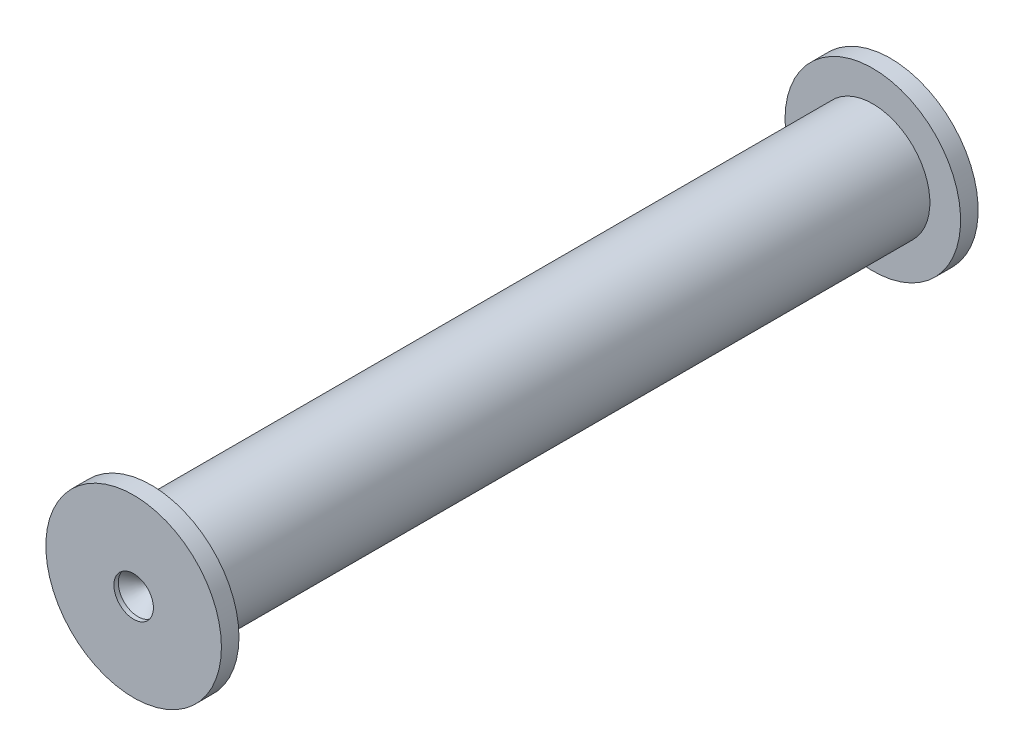
SolidWorks part; units mm, degrees
ref_plane "Ön Düzlem" through (0, 0, 0) normal (0, 0, 1) x (1, 0, 0)
ref_plane "Üst Düzlem" through (0, 0, 0) normal (0, 1, 0) x (1, 0, 0)
ref_plane "Sağ Düzlem" through (0, 0, 0) normal (1, 0, 0) x (0, 0, -1)
sketch "Çizim1" plane through (0, 0, 0) normal (0, 0, 1) x (1, 0, 0)
  circle A0 centre (3.3, -31.2819) radius 1.3
  dimension "D1" = 2.6
extrude "Yükseklik-Ekstrüzyon1" add sketch "Çizim1" against normal blind 16.34 and the other way blind 0.1
sketch "Çizim2" plane through (0, 0, 0.1) normal (0, 0, 1) x (1, 0, 0)
  circle A0 centre (3.3, -31.2819) radius 2
  dimension "D1" = 4
extrude "Yükseklik-Ekstrüzyon2" add sketch "Çizim2" along normal blind 0.4
sketch "Çizim3" plane through (0, 0, -16.34) normal (0, 0, -1) x (-1, 0, 0)
  circle A0 centre (-3.3, -31.2819) radius 2
  dimension "D1" = 4
extrude "Yükseklik-Ekstrüzyon3" add sketch "Çizim3" along normal blind 0.4
sketch "Çizim4" plane through (0, 0, -16.74) normal (0, 0, -1) x (-1, 0, 0)
  circle A0 centre (-3.3, -31.2819) radius 0.45
  dimension "D1" = 0.9
extrude "Kes-Ekstrüzyon1" cut sketch "Çizim4" against normal blind 0.5
chamfer "Pah1" distance 0.4 angle 45 1 edges at (2.85, -31.2819, -16.24)
sketch "Çizim5" plane through (0, 0, 0.5) normal (0, 0, 1) x (1, 0, 0)
  circle A0 centre (3.3, -31.2819) radius 0.45
  dimension "D1" = 0.9
extrude "Kes-Ekstrüzyon2" cut sketch "Çizim5" against normal blind 0.5
chamfer "Pah2" distance 0.4 angle 45 1 edges at (3.75, -31.2819, 0)
